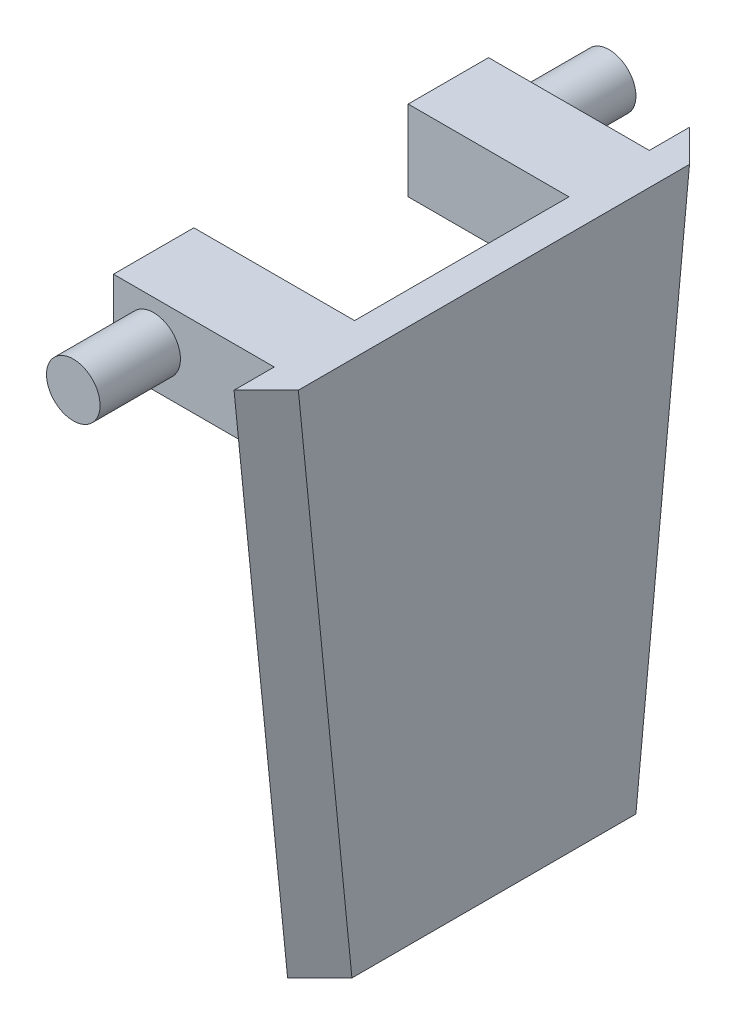
SolidWorks part; units mm, degrees
ref_plane "Alzado" through (0, 0, 0) normal (0, 0, 1) x (1, 0, 0)
ref_plane "Planta" through (0, 0, 0) normal (0, 1, 0) x (1, 0, 0)
ref_plane "Vista lateral" through (0, 0, 0) normal (1, 0, 0) x (0, 0, -1)
sketch "Croquis1" plane through (0, 0, 0) normal (1, 0, 0) x (0, 0, -1)
  line L0 (32.5, 0) -> (-32.5, 0)
  line L1 (-32.5, 0) -> (-42.5, 100)
  line L2 (-42.5, 100) -> (42.5, 100)
  line L3 (42.5, 100) -> (32.5, 0)
  point P3 (0, 100)
  dimension "D1" = 65
  dimension "D2" = 100
  dimension "D4" = 85
extrude "Saliente-Extruir1" add sketch "Croquis1" along normal blind 6
sketch "Croquis3" plane through (0, 0, 0) normal (-1, 0, 0) x (0, 0, 1)
  line L0 (0, 0) -> (0, 47.2048) construction
  line L1 (-42.5, 100) -> (42.5, 100) construction
  line L2 (-35, 100) -> (-20, 100)
  line L3 (-35, 100) -> (-35, 85)
  line L4 (-35, 85) -> (-20, 85)
  line L5 (-20, 100) -> (-20, 85)
  line L6 (35, 85) -> (20, 85)
  line L7 (20, 100) -> (20, 85)
  line L8 (35, 100) -> (20, 100)
  line L9 (35, 100) -> (35, 85)
  dimension "D1" = 15
  dimension "D2" = 15
  dimension "D3" = 20
extrude "Saliente-Extruir2" add sketch "Croquis3" along normal blind 30
sketch "Croquis4" plane through (0, 0, -35) normal (0, 0, -1) x (-1, 0, 0)
  line L0 (30, 100) -> (30, 85) construction
  circle A0 centre (22.5, 92.5383) radius 5
  point P5 (30, 92.5)
  dimension "D1" = 10
  dimension "D2" = 7.5
extrude "Saliente-Extruir3" add sketch "Croquis4" along normal blind 15
mirror "Simetría1" about plane through (0, 0, 0) normal (0, 0, 1) of "Saliente-Extruir3"
ref_plane "Plano1" through (0, -3.2178, -32.1782) normal (0, -0.0995, -0.995) x (-1, 0, 0)
sketch "Croquis7" plane through (0, 100, 0) normal (0, 1, 0) x (1, 0, 0)
  line L0 (0, -42.5) -> (6, -36.5)
  line L1 (6, 42.5) -> (6, -42.5) construction
  line L2 (6, -36.5) -> (6, -42.5)
  line L3 (6, -42.5) -> (0, -42.5)
  dimension "D1" = 45
sweep "Cortar-Barrer1" cut profiles "Croquis7" path edge at (6, 50, 37.5)
ref_plane "Plano2" through (0, 0, 0) normal (0, 0, 1) x (1, 0, 0)
sketch "Croquis8" plane through (0, 100, 0) normal (0, 1, 0) x (1, 0, 0)
  line L0 (0, 42.5) -> (6, 36.5)
  line L1 (6, 42.5) -> (6, -36.5) construction
  line L2 (6, 36.5) -> (6, 42.5)
  line L3 (6, 42.5) -> (0, 42.5)
  dimension "D1" = 45
sweep "Cortar-Barrer2" cut profiles "Croquis8" path edge at (6, 50, -37.5)
